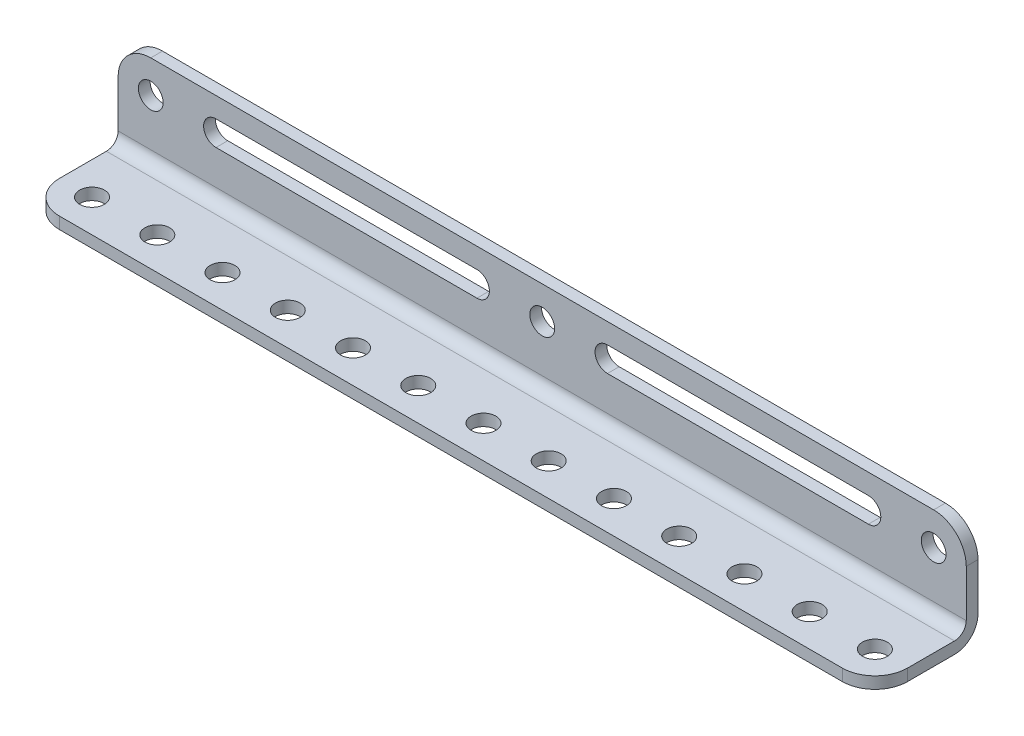
SolidWorks part; units mm, degrees
ref_plane "Front Plane" through (0, 0, 0) normal (0, 0, 1) x (1, 0, 0)
ref_plane "Top Plane" through (0, 0, 0) normal (0, 1, 0) x (1, 0, 0)
ref_plane "Right Plane" through (0, 0, 0) normal (1, 0, 0) x (0, 0, -1)
sketch "Sketch1" plane through (0, 0, 0) normal (1, 0, 0) x (0, 0, -1)
  line L0 (0, 0) -> (17.78, 0)
  line L1 (17.78, 0) -> (17.78, 17.78)
  dimension "D1" = 17.78
extrude "Extrude-Thin1" add sketch "Sketch1" along normal mid plane 165.1 thin
sketch "Sketch2" plane through (0, 0, 0) normal (0, 1, 0) x (-1, 0, 0)
  line L0 (-82.55, 0) -> (82.55, 0) construction
  circle A0 centre (76.2, -6.35) radius 2.413
  dimension "D3" = 4.826
  dimension "D1" = 76.2
  dimension "D2" = 6.35
extrude "Extrude2" cut sketch "Sketch2" against normal through all
pattern_linear "LPattern1" count 13 spacing 12.7 along (1, 0, 0) of "Extrude2"
fillet "Fillet1" radius 6.35 4 edges at (82.55, -1.143, 0) (82.55, 17.78, -18.923) (-82.55, -1.143, 0) (-82.55, 17.78, -18.923)
sketch "Sketch3" plane through (0, 0, -17.78) normal (0, 0, 1) x (1, 0, 0)
  line L0 (76.2, 17.78) -> (-76.2, 17.78) construction
  circle A0 centre (-76.2, 11.43) radius 2.413
  dimension "D3" = 4.826
  dimension "D1" = 76.2
  dimension "D2" = 6.35
extrude "Extrude3" cut sketch "Sketch3" against normal through all
pattern_linear "LPattern2" count 13 spacing 76.2 along (1, 0, 0) of "Extrude3"
sketch "Sketch4" plane through (0, 0, -17.78) normal (0, 0, 1) x (1, 0, 0)
  line L0 (0, 0) -> (0, 11.43) construction
  line L2 (-63.5, 13.843) -> (-12.7, 13.843)
  line L4 (-63.5, 9.017) -> (-12.7, 9.017)
  line L6 (63.5, 13.843) -> (12.7, 13.843)
  line L8 (63.5, 9.017) -> (12.7, 9.017)
  arc A0 (-63.5, 13.843) -> (-63.5, 9.017) centre (-63.5, 11.43) ccw
  arc A1 (63.5, 13.843) -> (63.5, 9.017) centre (63.5, 11.43) cw
  arc A2 (-12.7, 13.843) -> (-12.7, 9.017) centre (-12.7, 11.43) cw
  arc A3 (12.7, 13.843) -> (12.7, 9.017) centre (12.7, 11.43) ccw
  circle A4 centre (0, 11.43) radius 2.413 construction
  dimension "D1" = 25.4
  dimension "D2" = 50.8
extrude "Extrude4" cut sketch "Sketch4" against normal through all
